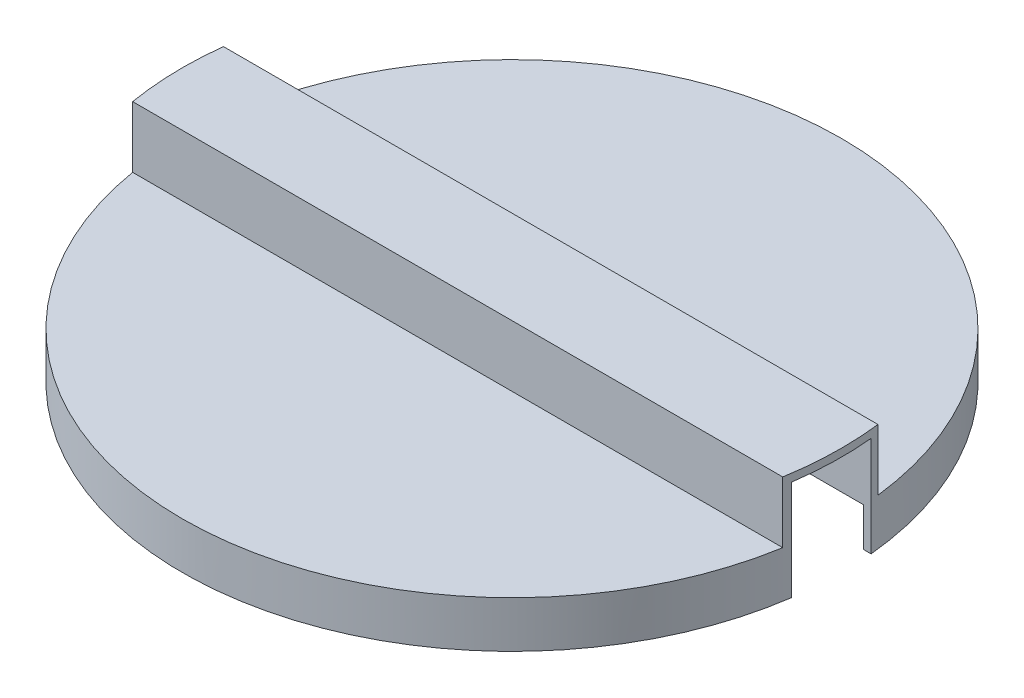
SolidWorks part; units mm, degrees
material "Acrylic (Medium-high impact)"
ref_plane "Front Plane" through (0, 0, 0) normal (0, 0, 1) x (1, 0, 0)
ref_plane "Top Plane" through (0, 0, 0) normal (0, 1, 0) x (1, 0, 0)
ref_plane "Right Plane" through (0, 0, 0) normal (1, 0, 0) x (0, 0, -1)
sketch "Sketch1" plane through (0, 0, 0) normal (0, 1, 0) x (1, 0, 0)
  line L0 (127.5, -3) -> (189.0789, -3) construction
  line L1 (-126.934, 12) -> (126.934, 12)
  line L2 (-126.223, -18) -> (126.223, -18)
  arc A0 (126.934, 12) -> (-126.934, 12) centre (0, 0) ccw
  arc A1 (-126.223, -18) -> (126.223, -18) centre (0, 0) ccw
  dimension "D1" = 255
  dimension "D2" = 30
  dimension "D3" = 15
extrude "Boss-Extrude1" add sketch "Sketch1" along normal blind 3
sketch "Sketch5" plane through (0, 3, 0) normal (0, 1, 0) x (1, 0, 0)
  line L0 (-126.6146, 15) -> (126.6146, 15)
  line L1 (-125.7587, -21) -> (125.7587, -21)
  line L2 (-126.934, 12) -> (126.934, 12)
  line L3 (-126.223, -18) -> (126.223, -18)
  arc A0 (126.934, 12) -> (126.6146, 15) centre (0, 0) ccw
  arc A1 (-126.934, 12) -> (-126.6146, 15) centre (0, 0) cw
  arc A2 (126.223, -18) -> (125.7587, -21) centre (0, 0) cw
  arc A3 (-126.223, -18) -> (-125.7587, -21) centre (0, 0) ccw
  arc A4 (126.934, 12) -> (-126.934, 12) centre (0, 0) ccw construction
  point P14 (126.3858, 16.819)
  dimension "D1" = 3
  dimension "D2" = 3
extrude "Boss-Extrude2" add sketch "Sketch5" along normal blind 20.7
sketch "Sketch6" plane through (0, 23.7, 0) normal (0, 1, 0) x (1, 0, 0)
  line L0 (-126.6146, 15) -> (126.6146, 15)
  line L1 (-125.7587, -21) -> (125.7587, -21)
  arc A0 (-126.6146, 15) -> (-125.7587, -21) centre (0, 0) ccw
  arc A1 (-126.223, -18) -> (-125.7587, -21) centre (0, 0) ccw construction
  arc A2 (125.7587, -21) -> (126.6146, 15) centre (0, 0) ccw
  arc A3 (126.934, 12) -> (126.6146, 15) centre (0, 0) ccw construction
extrude "Boss-Extrude3" add sketch "Sketch6" along normal blind 3
sketch "Sketch7" plane through (0, 0, 0) normal (0, -1, 0) x (1, 0, 0)
  line L0 (-126.934, -12) -> (126.934, -12) construction
  line L1 (-126.934, -12) -> (126.934, -12) construction
  line L2 (126.223, 18) -> (-126.223, 18) construction
  line L3 (-126.934, -12) -> (-123.9774, -12)
  line L4 (123.9774, -12) -> (126.934, -12)
  line L5 (123.1919, 18) -> (126.223, 18)
  line L6 (-126.223, 18) -> (-123.1919, 18)
  arc A0 (-126.934, -12) -> (126.934, -12) centre (0, 0) ccw
  arc A1 (126.223, 18) -> (-126.223, 18) centre (0, 0) ccw
  arc A2 (-126.223, 18) -> (-126.934, -12) centre (0, 0) ccw construction
  arc A3 (-123.9774, -12) -> (123.9774, -12) centre (0, 0) ccw
  arc A4 (123.1919, 18) -> (-123.1919, 18) centre (0, 0) ccw
  dimension "D1" = 124.5
extrude "Boss-Extrude4" add sketch "Sketch7" along normal blind 15
